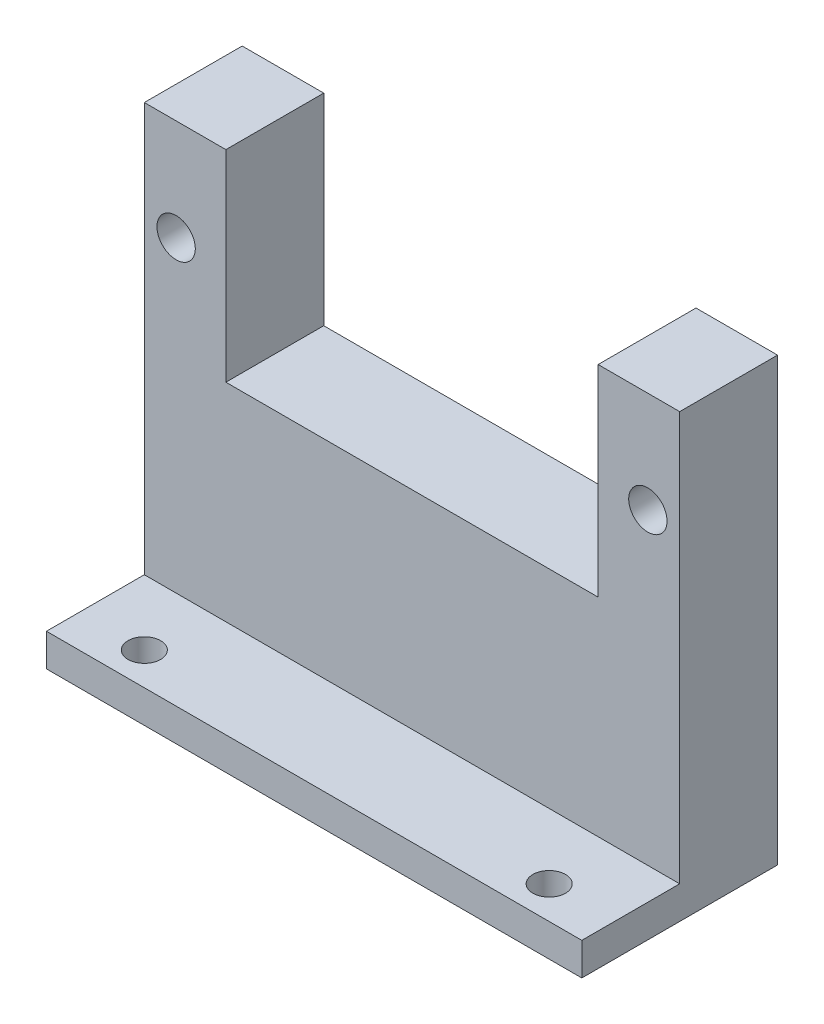
SolidWorks part; units mm, degrees
ref_plane "Front Plane" through (0, 0, 0) normal (0, 0, 1) x (1, 0, 0)
ref_plane "Top Plane" through (0, 0, 0) normal (0, 1, 0) x (1, 0, 0)
ref_plane "Right Plane" through (0, 0, 0) normal (1, 0, 0) x (0, 0, -1)
sketch "Sketch2" plane through (0, 0, 0) normal (0, 0, 1) x (1, 0, 0)
  line L0 (30.87, 27.07) -> (30.87, 20.87) construction
  line L1 (0, 0) -> (32.82, 0)
  line L2 (0, 0) -> (0, 20)
  line L3 (5, 14.72) -> (27.82, 14.72)
  line L4 (32.82, 0) -> (32.82, 14.72)
  line L6 (0, 20) -> (0, 27.07)
  line L7 (0, 27.07) -> (5, 27.07)
  line L8 (5, 14.72) -> (5, 27.07)
  line L10 (32.82, 14.72) -> (32.82, 27.07)
  line L11 (32.82, 27.07) -> (27.82, 27.07)
  line L12 (27.82, 14.72) -> (27.82, 27.07)
  line L13 (0, 2.9997) -> (32.82, 2.9997) construction
  line L14 (16.41, 30.0024) -> (16.41, 2.9997) construction
  circle A0 centre (30.87, 20.87) radius 1.175
  circle A1 centre (1.95, 20.87) radius 1.175
  point P18 (18.6287, 2.9997)
  point P19 (18.3515, 30.0024)
  point P20 (0, 0)
  dimension "D7" = 2.35
  dimension "D1" = 14.72
  dimension "D2" = 22.82
  dimension "D3" = 5
  dimension "D4" = 5
  dimension "D5" = 6.2
  dimension "D6" = 3.05
  dimension "D8" = 12.35
extrude "Boss-Extrude2" add sketch "Sketch2" along normal blind 6
sketch "Sketch4" plane through (0, 0, 0) normal (0, 1, 0) x (1, 0, 0)
  line L0 (32.82, -6) -> (32.82, 0) construction
  line L1 (0, -6) -> (32.82, -6)
  line L2 (0, -6) -> (0, -12)
  line L3 (0, -12) -> (32.82, -12)
  line L4 (32.82, -6) -> (32.82, -12)
  circle A0 centre (4, -10) radius 1
  circle A1 centre (28.82, -10) radius 1
  point P11 (0, 0)
  point P12 (2.9373, -10)
  point P13 (29.6646, -10)
  point P14 (0, 0)
  dimension "D1" = 2
  dimension "D2" = 4
  dimension "D3" = 6
  dimension "D4" = 4
  dimension "D5" = 4
extrude "Boss-Extrude3" add sketch "Sketch4" along normal blind 2
